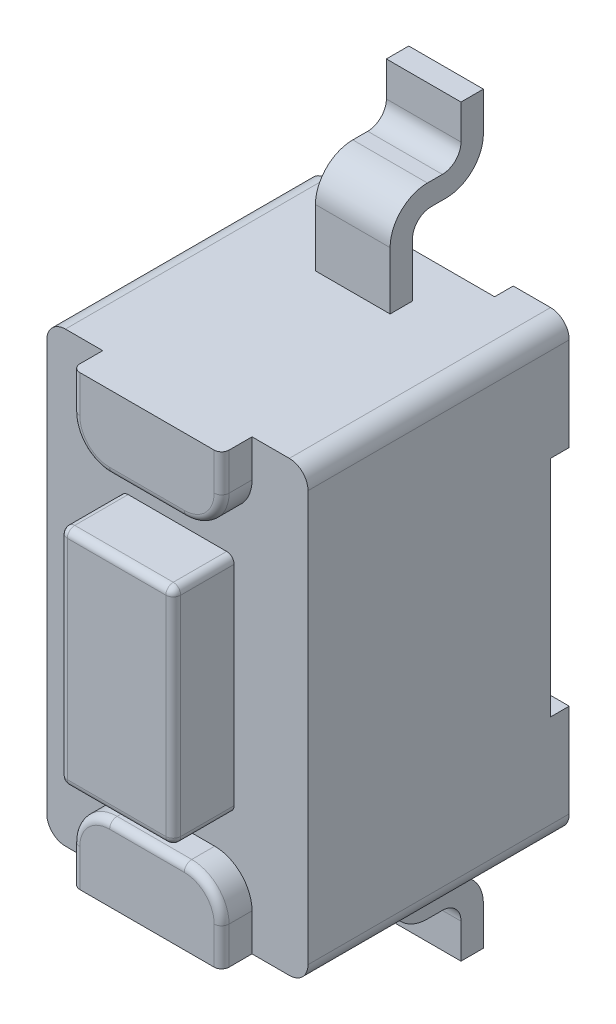
SolidWorks part; units mm, degrees
ref_plane "Front Plane" through (0, 0, 0) normal (0, 0, 1) x (1, 0, 0)
ref_plane "Top Plane" through (0, 0, 0) normal (0, 1, 0) x (1, 0, 0)
ref_plane "Right Plane" through (0, 0, 0) normal (1, 0, 0) x (0, 0, -1)
ref_plane "Plane1" through (0, 0, -4.065) normal (0, 0, -1) x (-1, 0, 0)
sketch "Sketch1" plane through (0, 0, -4.065) normal (0, 0, -1) x (-1, 0, 0)
  line L0 (1.75, -3) -> (1.75, 3)
  line L1 (1.75, 3) -> (-1.75, 3)
  line L2 (-1.75, 3) -> (-1.75, -3)
  line L3 (-1.75, -3) -> (1.75, -3)
extrude "Boss-Extrude1" add sketch "Sketch1" against normal blind 3.25
sketch "Sketch2" plane through (0, 3, 0) normal (0, 1, 0) x (-1, 0, 0)
  line L0 (-0.5, -3.165) -> (0.5, -3.165)
  line L1 (0.5, -3.165) -> (0.5, -3.465)
  line L2 (0.5, -3.465) -> (-0.5, -3.465)
  line L3 (-0.5, -3.465) -> (-0.5, -3.165)
extrude "Boss-Extrude2" add sketch "Sketch2" along normal blind 1.9845
sketch "Sketch3" plane through (0, 0, -3.465) normal (0, 0, -1) x (-1, 0, 0)
  line L0 (-0.5, 3.97) -> (-0.5, 4.9845)
  line L1 (-0.5, 4.9845) -> (0.5, 4.9845)
  line L2 (0.5, 4.9845) -> (0.5, 3.97)
  line L3 (0.5, 3.97) -> (-0.5, 3.97)
extrude "Boss-Extrude3" add sketch "Sketch3" along normal blind 0.95
sketch "Sketch4" plane through (0, -3, 0) normal (0, -1, 0) x (1, 0, 0)
  line L0 (-0.5, -3.165) -> (0.5, -3.165)
  line L1 (0.5, -3.165) -> (0.5, -3.465)
  line L2 (0.5, -3.465) -> (-0.5, -3.465)
  line L3 (-0.5, -3.465) -> (-0.5, -3.165)
extrude "Boss-Extrude4" add sketch "Sketch4" along normal blind 1.9845
sketch "Sketch5" plane through (0, 0, -3.465) normal (0, 0, -1) x (-1, 0, 0)
  line L0 (-0.5, -4.9845) -> (-0.5, -3.97)
  line L1 (-0.5, -3.97) -> (0.5, -3.97)
  line L2 (0.5, -3.97) -> (0.5, -4.9845)
  line L3 (0.5, -4.9845) -> (-0.5, -4.9845)
extrude "Boss-Extrude5" add sketch "Sketch5" along normal blind 0.95
sketch "Sketch6" plane through (0.5, 0, 0) normal (1, 0, 0) x (0, 0, -1)
  line L0 (4.115, 4.27) -> (4.115, 4.9845)
  line L1 (4.115, 4.9845) -> (3.165, 4.9845)
  line L2 (3.165, 4.9845) -> (3.165, 4.27)
  line L3 (3.165, 4.27) -> (4.115, 4.27)
extrude "Cut-Extrude1" cut sketch "Sketch6" against normal through all
sketch "Sketch7" plane through (0.5, 0, 0) normal (1, 0, 0) x (0, 0, -1)
  line L0 (4.115, -4.27) -> (3.165, -4.27)
  line L1 (3.165, -4.27) -> (3.165, -4.9845)
  line L2 (3.165, -4.9845) -> (4.115, -4.9845)
  line L3 (4.115, -4.9845) -> (4.115, -4.27)
extrude "Cut-Extrude2" cut sketch "Sketch7" against normal through all
sketch "Sketch8" plane through (0, 0, -4.065) normal (0, 0, -1) x (-1, 0, 0)
  line L0 (-1.75, 1.5) -> (-1.75, 3)
  line L1 (-1.75, 3) -> (-1, 3)
  line L2 (-1, 3) -> (-1, 1.5)
  line L3 (-1, 1.5) -> (-1.75, 1.5)
extrude "Boss-Extrude6" add sketch "Sketch8" along normal blind 0.25
sketch "Sketch9" plane through (0, 0, -4.065) normal (0, 0, -1) x (-1, 0, 0)
  line L0 (-1, -3) -> (-1.75, -3)
  line L1 (-1.75, -3) -> (-1.75, -1.5)
  line L2 (-1.75, -1.5) -> (-1, -1.5)
  line L3 (-1, -1.5) -> (-1, -3)
extrude "Boss-Extrude7" add sketch "Sketch9" along normal blind 0.25
sketch "Sketch10" plane through (0, 0, -4.065) normal (0, 0, -1) x (-1, 0, 0)
  line L0 (1, 3) -> (1.75, 3)
  line L1 (1.75, 3) -> (1.75, 1.5)
  line L2 (1.75, 1.5) -> (1, 1.5)
  line L3 (1, 1.5) -> (1, 3)
extrude "Boss-Extrude8" add sketch "Sketch10" along normal blind 0.25
sketch "Sketch11" plane through (0, 0, -4.065) normal (0, 0, -1) x (-1, 0, 0)
  line L0 (1.75, -1.5) -> (1.75, -3)
  line L1 (1.75, -3) -> (1, -3)
  line L2 (1, -3) -> (1, -1.5)
  line L3 (1, -1.5) -> (1.75, -1.5)
extrude "Boss-Extrude9" add sketch "Sketch11" along normal blind 0.25
sketch "Sketch12" plane through (0, 0, -0.815) normal (0, 0, 1) x (1, 0, 0)
  line L0 (-1, -3) -> (-1, -2)
  line L1 (-1, -2) -> (1, -2)
  line L2 (1, -2) -> (1, -3)
  line L3 (1, -3) -> (-1, -3)
extrude "Boss-Extrude10" add sketch "Sketch12" along normal blind 0.4075
sketch "Sketch13" plane through (0, 0, -0.815) normal (0, 0, 1) x (1, 0, 0)
  line L0 (1, 3) -> (1, 2)
  line L1 (1, 2) -> (-1, 2)
  line L2 (-1, 2) -> (-1, 3)
  line L3 (-1, 3) -> (1, 3)
extrude "Boss-Extrude11" add sketch "Sketch13" along normal blind 0.4075
sketch "Sketch14" plane through (0, 0, -0.815) normal (0, 0, 1) x (1, 0, 0)
  line L0 (-0.76, -1.5) -> (-0.76, 1.5)
  line L1 (-0.76, 1.5) -> (0.76, 1.5)
  line L2 (0.76, 1.5) -> (0.76, -1.5)
  line L3 (0.76, -1.5) -> (-0.76, -1.5)
extrude "Boss-Extrude12" add sketch "Sketch14" along normal blind 0.815
fillet "Fillet1" radius 0.5 8 edges at (0, 3.97, -4.415) (0, 4.27, -3.165) (0, -4.27, -3.165) (0, -3.97, -4.415) (-1, 2, -0.6113) (1, -2, -0.6113) (-1, -2, -0.6113) (1, 2, -0.6113)
fillet "Fillet2" radius 0.1 18 edges at (-0.76, -1.5, -0.4075) (0.76, -1.5, -0.4075) (0, -1.5, 0) (-0.76, 0, 0) (-0.76, 1.5, -0.4075) (0.76, 0, 0) (0, 1.5, 0) (0.76, 1.5, -0.4075) (-1, 2.75, -0.4075) (-0.8536, 2.1464, -0.4075) (0, 2, -0.4075) (0.8536, 2.1464, -0.4075) (1, 2.75, -0.4075) (1, -2.75, -0.4075) (0.8536, -2.1464, -0.4075) (0, -2, -0.4075) (-1, -2.75, -0.4075) (-0.8536, -2.1464, -0.4075)
fillet "Fillet3" radius 0.25 8 edges at (0, -4.27, -4.115) (-1.75, -3, -2.565) (-1.75, 3, -2.565) (1.75, -3, -2.565) (1.75, 3, -2.565) (0, 4.27, -4.115) (0, -3.97, -3.465) (0, 3.97, -3.465)
